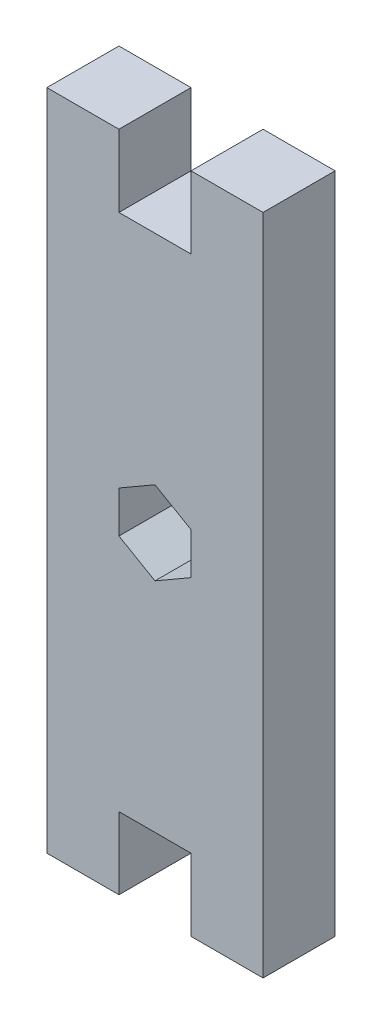
SolidWorks part; units mm, degrees
ref_plane "Plan de face" through (0, 0, 0) normal (0, 0, 1) x (1, 0, 0)
ref_plane "Plan de dessus" through (0, 0, 0) normal (0, 1, 0) x (1, 0, 0)
ref_plane "Plan de droite" through (0, 0, 0) normal (1, 0, 0) x (0, 0, -1)
sketch "Esquisse1" plane through (0, 0, 0) normal (0, 0, 1) x (1, 0, 0)
  line L0 (3.4681, 2.9254) -> (8.4681, 2.9254)
  line L1 (-6.5319, 2.9254) -> (-1.5319, 2.9254)
  line L2 (-6.5319, 2.9254) -> (-6.5319, -43.0746)
  line L3 (-6.5319, -43.0746) -> (-1.5319, -43.0746)
  line L4 (8.4681, 2.9254) -> (8.4681, -43.0746)
  line L6 (-1.5319, 2.9254) -> (-1.5319, -2.0746)
  line L7 (-1.5319, -2.0746) -> (3.4681, -2.0746)
  line L8 (3.4681, 2.9254) -> (3.4681, -2.0746)
  line L10 (3.4681, -43.0746) -> (3.4681, -38.0746)
  line L11 (-1.5319, -38.0746) -> (3.4681, -38.0746)
  line L12 (-1.5319, -43.0746) -> (-1.5319, -38.0746)
  line L13 (3.4681, -43.0746) -> (8.4681, -43.0746)
  dimension "D1" = 15
  dimension "D2" = 46
  dimension "D3" = 5
  dimension "D5" = 5
extrude "Boss.-Extru.1" add sketch "Esquisse1" along normal blind 5
sketch "Esquisse2" plane through (0, 0, 0) normal (0, 0, -1) x (-1, 0, 0)
  line L1 (-3.4681, -21.5179) -> (-0.9681, -22.9613)
  line L2 (-0.9681, -22.9613) -> (1.5319, -21.5179)
  line L3 (1.5319, -21.5179) -> (1.5319, -18.6312)
  line L4 (1.5319, -18.6312) -> (-0.9681, -17.1878)
  line L5 (-0.9681, -17.1878) -> (-3.4681, -18.6312)
  line L6 (-3.4681, -18.6312) -> (-3.4681, -21.5179)
  circle A0 centre (-0.9681, -20.0746) radius 2.5 construction
  dimension "D1" = 5
extrude "Cut-Extrude1" cut sketch "Esquisse2" against normal blind 10
